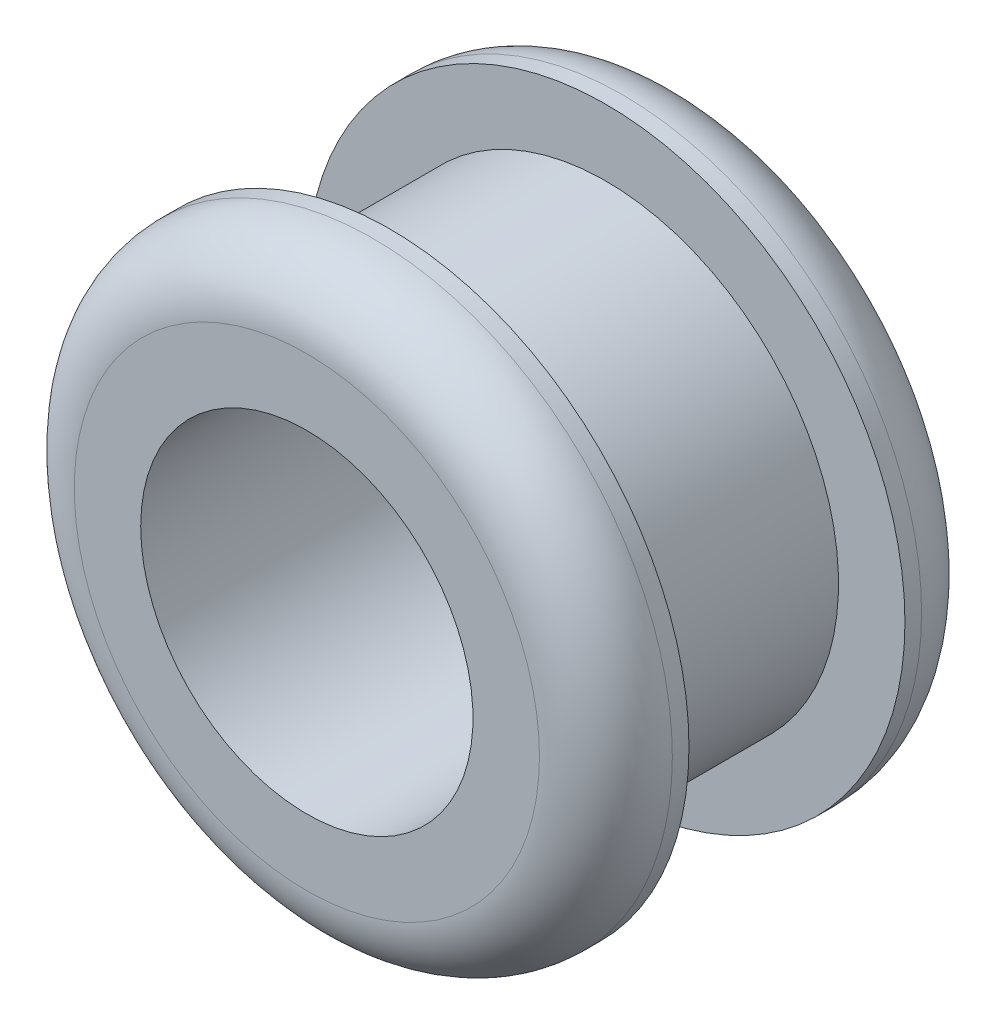
SolidWorks part; units mm, degrees
ref_plane "Front Plane" through (0, 0, 0) normal (0, 0, 1) x (1, 0, 0)
ref_plane "Top Plane" through (0, 0, 0) normal (0, 1, 0) x (1, 0, 0)
ref_plane "Right Plane" through (0, 0, 0) normal (1, 0, 0) x (0, 0, -1)
sketch "Sketch1" plane through (0, 0, 0) normal (0, 0, 1) x (1, 0, 0)
  circle A0 centre (0, 0) radius 5
  circle A1 centre (0, 0) radius 7
  dimension "D1" = 10
  dimension "D2" = 14
extrude "Boss-Extrude1" add sketch "Sketch1" along normal mid plane 6.5
sketch "Sketch2" plane through (0, 0, 3.25) normal (0, 0, 1) x (1, 0, 0)
  circle A0 centre (0, 0) radius 5
  circle A1 centre (0, 0) radius 9
  dimension "D1" = 18
  dimension "D2" = 10
extrude "Boss-Extrude2" add sketch "Sketch2" along normal blind 2.5
fillet "Fillet1" radius 2 1 edges at (9, 0, 5.75)
mirror "Mirror1" about plane through (0, 0, 0) normal (0, 0, 1) of "Fillet1", "Boss-Extrude2"
